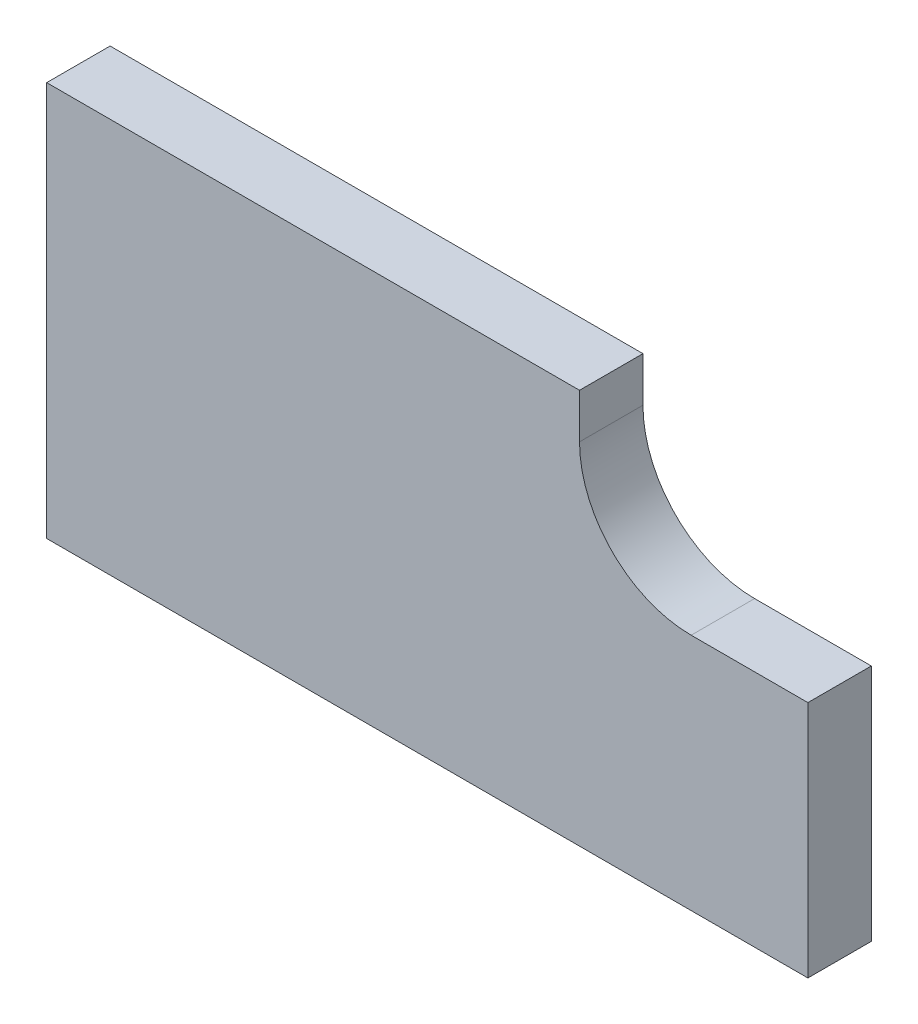
SolidWorks part; units mm, degrees
ref_plane "Front Plane" through (0, 0, 0) normal (0, 0, 1) x (1, 0, 0)
ref_plane "Top Plane" through (0, 0, 0) normal (0, 1, 0) x (1, 0, 0)
ref_plane "Right Plane" through (0, 0, 0) normal (1, 0, 0) x (0, 0, -1)
sketch "Sketch1" plane through (0, 0, 0) normal (0, 0, 1) x (1, 0, 0)
  line L1 (127, 47) -> (150, 47)
  line L2 (150, 47) -> (150, 0)
  line L3 (150, 0) -> (0, 0)
  line L4 (0, 0) -> (0, 69)
  line L5 (0, 69) -> (0, 92)
  line L6 (0, 92) -> (105, 92)
  line L7 (105, 92) -> (105, 69)
  arc A0 (105, 69) -> (127, 47) centre (127, 69) ccw
  dimension "D3" = 22
  dimension "D1" = 150
  dimension "D2" = 69
  dimension "D4" = 47
  dimension "D5" = 23
  dimension "D6" = 23
  dimension "D7" = 23
extrude "Boss-Extrude1" add sketch "Sketch1" along normal blind 5.5
sketch "Sketch2" plane through (0, 0, 5.5) normal (0, 0, 1) x (1, 0, 0)
  line L6 (0, 92) -> (0, 0)
  line L7 (0, 0) -> (150, 0)
  line L8 (150, 0) -> (150, 47)
  line L9 (150, 47) -> (127, 47)
  line L10 (105, 69) -> (105, 92)
  line L11 (105, 92) -> (0, 92)
  line L12 (0, 92) -> (0, 0)
  line L13 (0, 0) -> (150, 0)
  line L14 (150, 0) -> (150, 47)
  line L15 (150, 47) -> (127, 47)
  line L16 (105, 69) -> (105, 92)
  line L17 (105, 92) -> (0, 92)
  arc A1 (105, 69) -> (127, 47) centre (127, 69) ccw
  arc A2 (105, 69) -> (127, 47) centre (127, 69) ccw
  dimension "D1" = 0
extrude "Boss-Extrude2" add sketch "Sketch2" along normal blind 7
sketch "Sketch3" plane through (0, 0, 12.5) normal (0, 0, 1) x (1, 0, 0)
  line L0 (0, 92) -> (0, 0) construction
  line L1 (0, 77.8) -> (105, 77.8)
  line L2 (0, 77.8) -> (0, 92)
  line L3 (0, 92) -> (105, 92)
  line L4 (105, 77.8) -> (105, 92)
  dimension "D1" = 14.2
extrude "Cut-Extrude1" cut sketch "Sketch3" against normal through all
